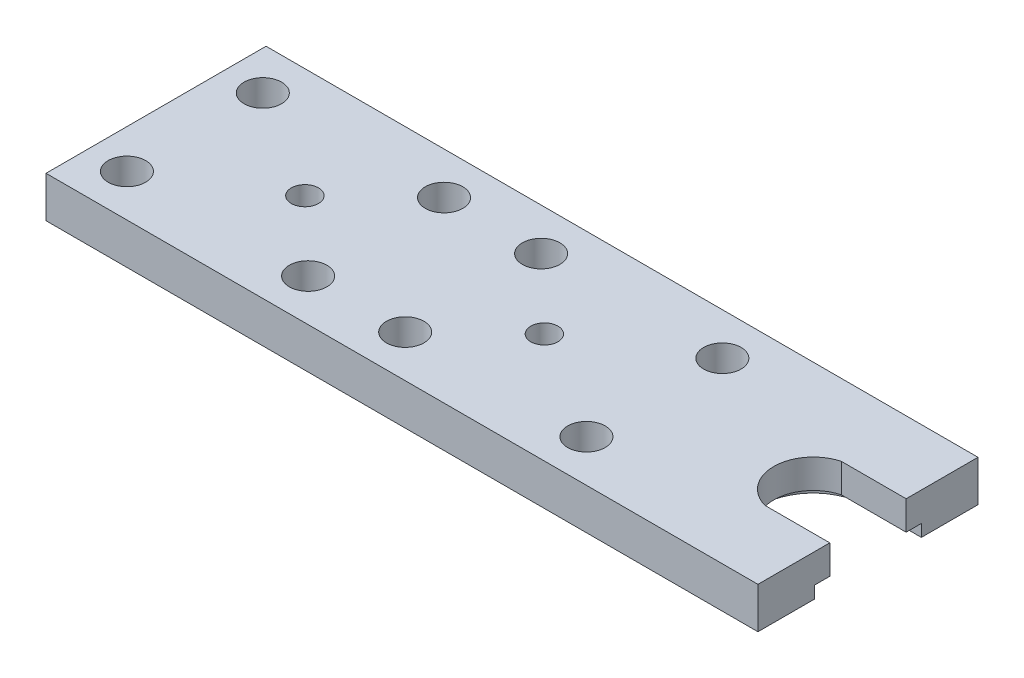
SolidWorks part; units mm, degrees
ref_plane "Front Plane" through (0, 0, 0) normal (0, 0, 1) x (1, 0, 0)
ref_plane "Top Plane" through (0, 0, 0) normal (0, 1, 0) x (1, 0, 0)
ref_plane "Right Plane" through (0, 0, 0) normal (1, 0, 0) x (0, 0, -1)
ref_plane "Plane1" through (0, 0, 0) normal (0, -1, 0) x (1, 0, 0)
sketch "Sketch1" plane through (0, 0, 0) normal (0, -1, 0) x (1, 0, 0)
  line L0 (-41.5, -1) -> (68.5, -1)
  line L1 (68.5, -1) -> (68.5, 33)
  line L2 (68.5, 33) -> (-41.5, 33)
  line L3 (-41.5, 33) -> (-41.5, -1)
  dimension "D4" = 110
  dimension "D6" = 34
extrude "Boss-Extrude1" add sketch "Sketch1" against normal blind 6.35
sketch "Sketch2" plane through (0, 6.35, 0) normal (0, 1, 0) x (1, 0, 0)
  line L0 (-41.5, -16) -> (68.5, -16) construction
  line L1 (-41.5, -33) -> (-41.5, 1) construction
  line L2 (68.5, 1) -> (68.5, -33) construction
  line L3 (-41.5, -5.5) -> (68.5, -5.5) construction
  line L4 (-7.5, -5.5) -> (7.5, -5.5) construction
  line L5 (-7.5, -5.5) -> (7.5, -5.5) construction
  line L6 (0, 1) -> (0, -33) construction
  line L7 (-41.5, 1) -> (68.5, 1) construction
  line L8 (-35.5, -5.5) -> (-7.5, -5.5) construction
  line L9 (7.5, -5.5) -> (35.5, -5.5) construction
  line L10 (68.5, -33) -> (-41.5, -33) construction
  point P2 (35.5, -26.5)
  point P3 (7.5, -26.5)
  point P8 (-35.5, -5.5)
  point P10 (-7.5, -5.5)
  point P12 (7.5, -5.5)
  point P13 (35.5, -5.5)
  point P14 (-7.5, -26.5)
  point P15 (-35.5, -26.5)
  point P18 (0, -5.5)
  point P25 (-18.5, -16)
  point P26 (18.5, -16)
  point P28 (-21.5, -5.5)
  point P31 (21.5, -5.5)
  dimension "D1" = 28
  dimension "D2" = 15
  dimension "D3" = 28
  dimension "D4" = 37
  dimension "D5" = 6
  dimension "D6" = 21
hole_wizard "M5 Clearance Hole1" positions "Sketch4" profile "Sketch3" hole size "M5" standard "ANSI Metric" end condition through all
sketch "Sketch4" plane through (0, 6.35, 0) normal (0, 1, 0) x (1, 0, 0)
  point P0 (-35.5, -5.5)
  point P3 (-7.5, -5.5)
  point P6 (7.5, -5.5)
  point P9 (35.5, -5.5)
  point P12 (-35.5, -26.5)
  point P15 (-7.5, -26.5)
  point P18 (7.5, -26.5)
  point P21 (35.5, -26.5)
sketch "Sketch3" plane through (-35.5, 6.35, 5.5) normal (1, 0, 0) x (0, 0, 1)
  line L0 (0, 0) -> (0, 6.35)
  line L1 (0, 6.35) -> (2.9, 6.35)
  line L2 (2.9, 6.35) -> (2.9, 0)
  line L5 (2.9, 0) -> (0, 0)
  line L11 (0, -6.35) -> (0, 107.95) construction
  dimension "Thru Hole Dia." = 5.8
  dimension "Thru Hole Depth" = 6.35
hole_wizard "Tap Drill for M5x0.8 Tap1" positions "Sketch7" profile "Sketch8" hole size "M5x0.8" standard "ANSI Metric" end condition through all
sketch "Sketch7" plane through (0, 6.35, 0) normal (0, 1, 0) x (1, 0, 0)
  point P0 (-18.5, -16)
  point P3 (18.5, -16)
sketch "Sketch8" plane through (-18.5, 6.35, 16) normal (1, 0, 0) x (0, 0, 1)
  line L0 (0, 0) -> (0, 6.35)
  line L1 (0, 6.35) -> (2.1, 6.35)
  line L2 (2.1, 6.35) -> (2.1, 0)
  line L5 (2.1, 0) -> (0, 0)
  line L11 (0, -6.35) -> (0, 107.95) construction
  dimension "Thru Hole Dia." = 4.2
  dimension "Thru Hole Depth" = 6.35
sketch "Sketch9" plane through (0, 6.35, 0) normal (0, 1, 0) x (1, 0, 0)
  line L0 (68.5, -16) -> (53.9492, -16) construction
  line L1 (68.5, 1) -> (68.5, -33) construction
  line L2 (68.5, -10.1) -> (58.5, -10.1)
  line L3 (68.5, -21.9) -> (58.5, -21.9)
  line L4 (68.5, -10.1) -> (68.5, -21.9)
  arc A0 (58.5, -10.1) -> (58.5, -21.9) centre (60.0492, -16) ccw
  dimension "D2" = 6.1
  dimension "D1" = 11.8
  dimension "D3" = 10
extrude "Cut-Extrude1" cut sketch "Sketch9" against normal through all
sketch "Sketch10" plane through (0, 0, 0) normal (0, 1, 0) x (1, 0, 0)
  line L0 (68.5, -33) -> (68.5, 1) construction
  line L1 (68.5, -16) -> (51.5984, -16) construction
  line L2 (68.5, -24.25) -> (60.0492, -24.25)
  line L3 (68.5, -7.75) -> (60.0492, -7.75)
  line L4 (68.5, -7.75) -> (68.5, -24.25)
  arc A0 (60.0492, -24.25) -> (60.0492, -7.75) centre (60.0492, -16) cw
  point P11 (60.0492, -16)
  dimension "D1" = 16.5
extrude "Cut-Extrude2" cut sketch "Sketch10" along normal blind 1.87
equation "\"D3\"=0.393701"
